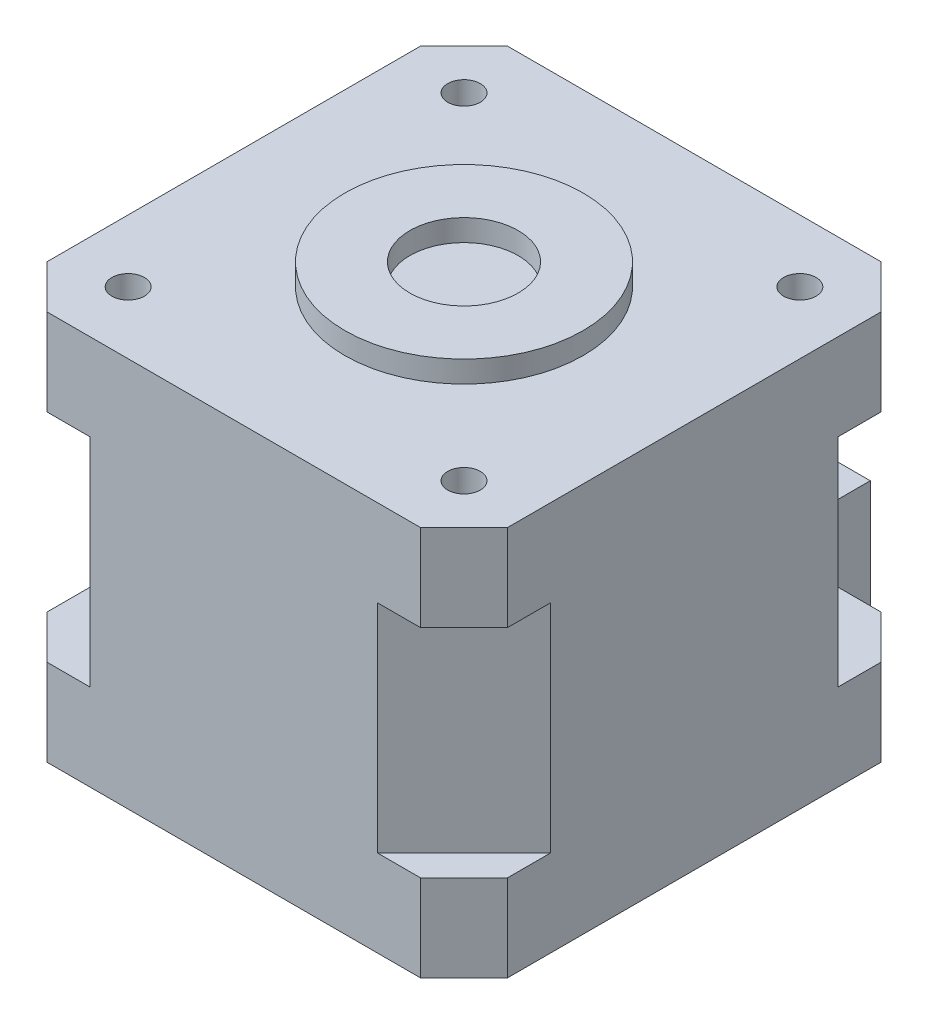
SolidWorks part; units mm, degrees
ref_plane "Спереди" through (0, 0, 0) normal (0, 0, 1) x (1, 0, 0)
ref_plane "Сверху" through (0, 0, 0) normal (0, 1, 0) x (1, 0, 0)
ref_plane "Справа" through (0, 0, 0) normal (1, 0, 0) x (0, 0, -1)
sketch "Эскиз1" plane through (0, 0, 0) normal (0, 1, 0) x (1, 0, 0)
  line L0 (-13.25, 21.25) -> (-21.25, 13.25)
  line L1 (13.25, 21.25) -> (-13.25, 21.25)
  line L2 (21.25, 13.25) -> (21.25, -13.25)
  line L3 (13.25, -21.25) -> (-13.25, -21.25)
  line L4 (-21.25, 13.25) -> (-21.25, -13.25)
  line L5 (21.25, 21.25) -> (-21.25, -21.25) construction
  line L6 (21.25, -21.25) -> (-21.25, 21.25) construction
  line L7 (-21.25, -13.25) -> (-13.25, -21.25)
  line L8 (13.25, 21.25) -> (21.25, 13.25)
  line L9 (21.25, -13.25) -> (13.25, -21.25)
  point P0 (0, 0)
  dimension "D1" = 42.5
extrude "Бобышка-Вытянуть1" add sketch "Эскиз1" along normal mid plane 20
sketch "Эскиз2" plane through (0, 10, 0) normal (0, 1, 0) x (1, 0, 0)
  line L0 (-17.25, 21.25) -> (-21.25, 17.25)
  line L1 (17.25, 21.25) -> (-17.25, 21.25)
  line L2 (21.25, 17.25) -> (21.25, -17.25)
  line L3 (17.25, -21.25) -> (-17.25, -21.25)
  line L4 (-21.25, 17.25) -> (-21.25, -17.25)
  line L5 (21.25, 21.25) -> (-21.25, -21.25) construction
  line L6 (21.25, -21.25) -> (0, 0) construction
  line L7 (21.25, 17.25) -> (17.25, 21.25)
  line L8 (21.25, -17.25) -> (17.25, -21.25)
  line L9 (-21.25, -17.25) -> (-17.25, -21.25)
  line L10 (-19.25, 19.25) -> (-21.25, 21.25) construction
  line L11 (0, 0) -> (-15.5, 15.5) construction
  line L12 (0, 21.25) -> (0, -21.25) construction
  line L13 (-15.5, 15.5) -> (15.5, 15.5) construction
  line L14 (-21.25, 0) -> (21.25, 0) construction
  circle A0 centre (-15.5, 15.5) radius 1.5
  circle A1 centre (15.5, 15.5) radius 1.5
  circle A2 centre (15.5, -15.5) radius 1.5
  circle A3 centre (-15.5, -15.5) radius 1.5
  point P0 (0, 0)
  dimension "D3" = 3
  dimension "D1" = 42.5
  dimension "D2" = 42.5
  dimension "D4" = 31
extrude "Бобышка-Вытянуть2" add sketch "Эскиз2" along normal blind 8
mirror "Зеркальное отражение1" about plane through (0, 0, 0) normal (0, 1, 0) of "Бобышка-Вытянуть2"
sketch "Эскиз3" plane through (0, 0, -21.25) normal (0, 0, -1) x (-1, 0, 0)
  line L0 (0, -18) -> (0, 18) construction
  line L1 (-17.25, -18) -> (17.25, -18) construction
  line L2 (-17.25, 18) -> (17.25, 18) construction
  line L3 (8.25, -18) -> (8.25, -8)
  line L4 (8.25, -18) -> (-8.25, -18)
  line L6 (8.25, -8) -> (-8.25, -8)
  line L7 (-8.25, -18) -> (-8.25, -8)
  point P11 (0, -8)
  dimension "D1" = 8.25
  dimension "D2" = 10
extrude "Бобышка-Вытянуть3" add sketch "Эскиз3" along normal blind 8
sketch "Эскиз4" plane through (0, 18, 0) normal (0, 1, 0) x (1, 0, 0)
  circle A0 centre (0, 0) radius 5
  circle A1 centre (0, 0) radius 11
  dimension "D1" = 10
  dimension "D2" = 22
extrude "Бобышка-Вытянуть4" add sketch "Эскиз4" along normal blind 2
